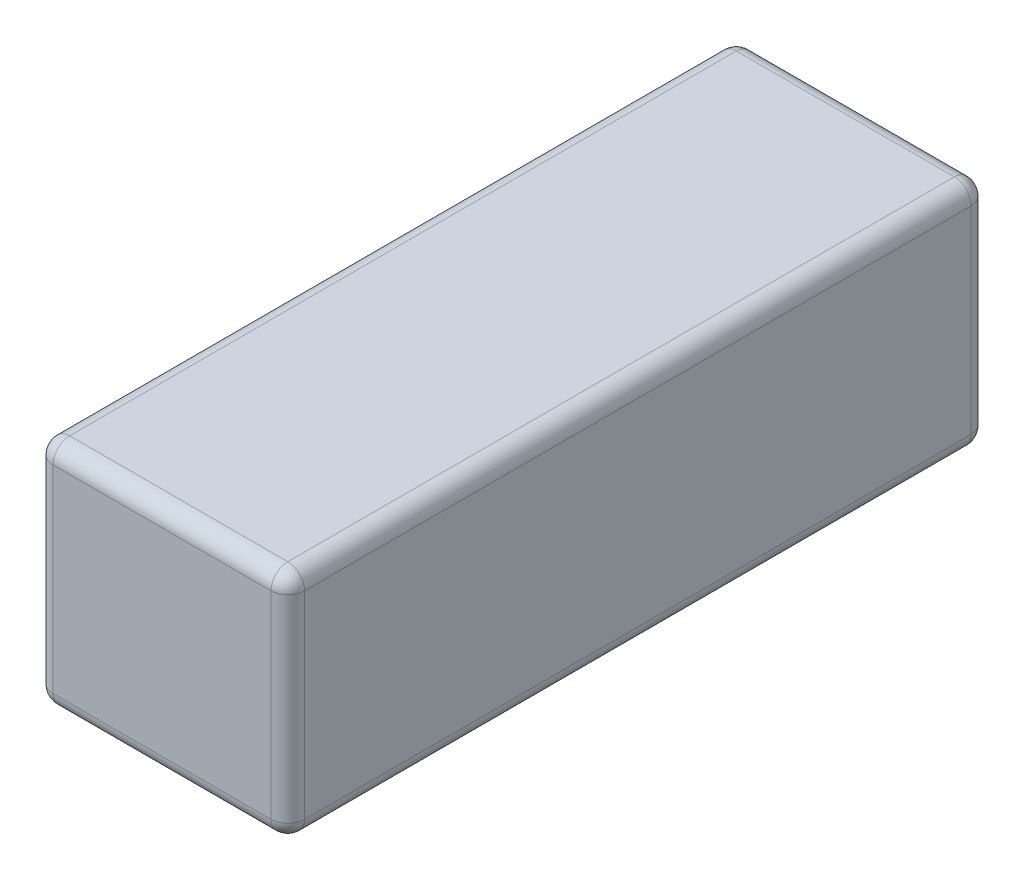
SolidWorks part; units mm, degrees
ref_plane "Front Plane" through (0, 0, 0) normal (0, 0, 1) x (1, 0, 0)
ref_plane "Top Plane" through (0, 0, 0) normal (0, 1, 0) x (1, 0, 0)
ref_plane "Right Plane" through (0, 0, 0) normal (1, 0, 0) x (0, 0, -1)
sketch "Sketch1" plane through (0, 0, 0) normal (0, 1, 0) x (1, 0, 0)
  line L1 (-28.6254, 12.7376) -> (9.4746, 12.7376)
  line L2 (-28.6254, 12.7376) -> (-28.6254, -93.2624)
  line L3 (-28.6254, -93.2624) -> (9.4746, -93.2624)
  line L4 (9.4746, 12.7376) -> (9.4746, -93.2624)
  dimension "D1" = 106
  dimension "D2" = 38.1
extrude "Boss-Extrude1" add sketch "Sketch1" along normal blind 35.052
fillet "Fillet1" radius 2.54 12 edges at (-28.6254, 17.526, 93.2624) (-9.5754, 0, 93.2624) (-28.6254, 0, 40.2624) (-9.5754, 35.052, 93.2624) (-28.6254, 35.052, 40.2624) (-9.5754, 35.052, -12.7376) (-28.6254, 17.526, -12.7376) (-9.5754, 0, -12.7376) (9.4746, 17.526, 93.2624) (9.4746, 35.052, 40.2624) (9.4746, 17.526, -12.7376) (9.4746, 0, 40.2624)
